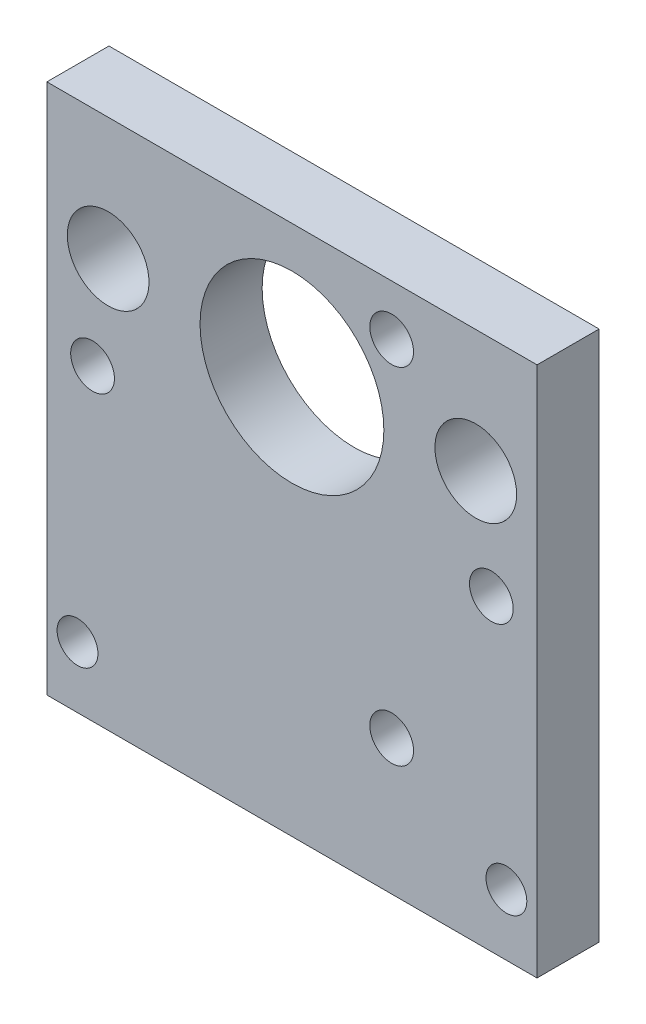
SolidWorks part; units mm, degrees
material "6063-O"
ref_plane "Front" through (0, 0, 0) normal (0, 0, 1) x (1, 0, 0)
ref_plane "Top" through (0, 0, 0) normal (0, 1, 0) x (1, 0, 0)
ref_plane "Right" through (0, 0, 0) normal (1, 0, 0) x (0, 0, -1)
sketch "Sketch1" plane through (0, 0, 0) normal (0, 0, 1) x (1, 0, 0)
  line L1 (19.05, -20.6375) -> (-19.05, -20.6375)
  line L2 (19.05, -20.6375) -> (19.05, 20.6375)
  line L3 (19.05, 20.6375) -> (-19.05, 20.6375)
  line L4 (-19.05, -20.6375) -> (-19.05, 20.6375)
  line L5 (19.05, -20.6375) -> (-19.05, 20.6375) construction
  line L6 (19.05, 20.6375) -> (-19.05, -20.6375) construction
  point P0 (0, 0)
  dimension "D1" = 38.1
  dimension "D2" = 41.275
extrude "Boss-Extrude1" add sketch "Sketch1" along normal blind 4.826
sketch "Sketch2" plane through (0, 0, 4.826) normal (0, 0, 1) x (1, 0, 0)
  line L0 (19.05, 20.6375) -> (-19.05, 20.6375) construction
  line L1 (0, 0) -> (0, 18.787) construction
  line L2 (-15.5, 3.287) -> (15.5, 3.287) construction
  line L3 (7.75, -10.1364) -> (0, 3.287) construction
  line L4 (0, 3.287) -> (7.75, 16.7104) construction
  line L5 (-14.2875, 11.1125) -> (14.2875, 11.1125) construction
  line L6 (-19.05, 20.6375) -> (-19.05, -20.6375) construction
  circle A0 centre (0, 10.287) radius 7.1438
  circle A1 centre (0, 3.287) radius 15.5 construction
  circle A4 centre (7.75, 16.7104) radius 1.7
  circle A5 centre (7.75, -10.1364) radius 1.7
  circle A6 centre (-15.5, 3.287) radius 1.7
  circle A7 centre (15.5, 3.287) radius 1.7
  circle A8 centre (-14.2875, 11.1125) radius 3.175
  circle A9 centre (14.2875, 11.1125) radius 3.175
  point P23 (0, 11.1125)
  dimension "D2" = 14.2875
  dimension "D3" = 31
  dimension "D5" = 3.4
  dimension "D10" = 6.35
  dimension "D1" = 10.3505
  dimension "D4" = 7
  dimension "D6" = 120
  dimension "D7" = 30
  dimension "D8" = 9.525
  dimension "D9" = 4.7625
extrude "Cut-Extrude1" cut sketch "Sketch2" against normal through all contours A0
hole_wizard "Ø3.4 (3.4) Diameter Hole1" positions "Sketch3" profile "Sketch4" hole size "Ø3.4" standard "ANSI Metric" end condition through all
sketch "Sketch3" plane through (0, 0, 4.826) normal (0, 0, 1) x (1, 0, 0)
  point P0 (-15.5, 3.287)
  point P3 (7.75, 16.7104)
  point P6 (15.5, 3.287)
  point P9 (7.75, -10.1364)
sketch "Sketch4" plane through (-15.5, 3.287, 4.826) normal (1, 0, 0) x (0, -1, 0)
  line L0 (0, 0) -> (0, 4.826)
  line L1 (0, 4.826) -> (1.7, 4.826)
  line L2 (1.7, 4.826) -> (1.7, 0)
  line L5 (1.7, 0) -> (0, 0)
  line L11 (0, -6.35) -> (0, 107.95) construction
  dimension "Thru Hole Dia." = 3.4
  dimension "Thru Hole Depth" = 4.826
hole_wizard "1/4 (0.25) Diameter Hole1" positions "Sketch5" profile "Sketch6" hole size "1/4" standard "ANSI Inch" end condition through all
sketch "Sketch5" plane through (0, 0, 4.826) normal (0, 0, 1) x (1, 0, 0)
  point P0 (-14.2875, 11.1125)
  point P3 (14.2875, 11.1125)
sketch "Sketch6" plane through (-14.2875, 11.1125, 4.826) normal (1, 0, 0) x (0, -1, 0)
  line L0 (0, 0) -> (0, 4.826)
  line L1 (0, 4.826) -> (3.175, 4.826)
  line L2 (3.175, 4.826) -> (3.175, 0)
  line L5 (3.175, 0) -> (0, 0)
  line L11 (0, -6.35) -> (0, 107.95) construction
  dimension "Thru Hole Dia." = 6.35
  dimension "Thru Hole Depth" = 4.826
sketch "Sketch7" plane through (0, 0, 4.826) normal (0, 0, 1) x (1, 0, 0)
  line L0 (-16.6687, -15.875) -> (16.6688, -15.875) construction
  line L3 (-19.05, -20.6375) -> (19.05, -20.6375) construction
  line L4 (0, 0) -> (0, -15.875) construction
  circle A0 centre (-16.6687, -15.875) radius 1.5875
  circle A1 centre (16.6688, -15.875) radius 1.5875
  point P1 (8.1358, -15.875)
  point P2 (-19.05, -15.875)
  point P3 (0, 0)
  point P4 (0, 0)
  point P5 (-8.8584, -15.875)
  dimension "D1" = 3.175
  dimension "D2" = 4.7625
  dimension "D3" = 33.3375
hole_wizard "1/8 (0.125) Clearance Dowel Hole1" positions "Sketch10" profile "Sketch11" hole size "1/8" standard "ANSI Inch" end condition through all
sketch "Sketch10" plane through (0, 0, 4.826) normal (0, 0, 1) x (1, 0, 0)
  point P0 (-16.6687, -15.875)
  point P3 (16.6688, -15.875)
sketch "Sketch11" plane through (-16.6687, -15.875, 4.826) normal (1, 0, 0) x (0, -1, 0)
  line L0 (0, 0) -> (0, 4.826)
  line L1 (0, 4.826) -> (1.5875, 4.826)
  line L2 (1.5875, 4.826) -> (1.5875, 0)
  line L5 (1.5875, 0) -> (0, 0)
  line L11 (0, -6.35) -> (0, 107.95) construction
  dimension "Thru Hole Dia." = 3.175
  dimension "Thru Hole Depth" = 4.826
